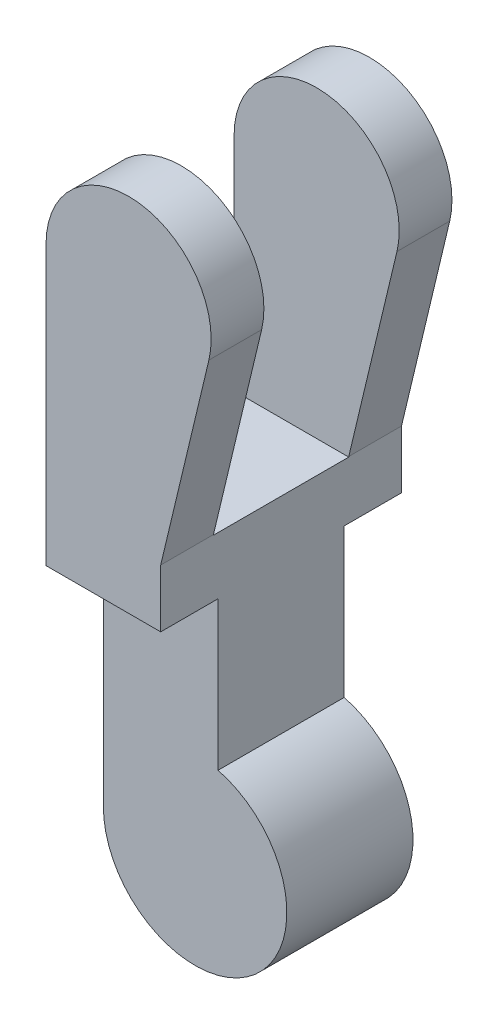
SolidWorks part; units mm, degrees
ref_plane "Front Plane" through (0, 0, 0) normal (0, 0, 1) x (1, 0, 0)
ref_plane "Top Plane" through (0, 0, 0) normal (0, 1, 0) x (1, 0, 0)
ref_plane "Right Plane" through (0, 0, 0) normal (1, 0, 0) x (0, 0, -1)
sketch "Sketch1" plane through (0, 0, 0) normal (0, 0, 1) x (1, 0, 0)
  line L0 (-80, 0) -> (-80, 450)
  line L1 (20, 257.4597) -> (20, 77.4597)
  line L2 (20, 257.4597) -> (62.0268, 433.2594)
  arc A0 (-80, 0) -> (20, 77.4597) centre (0, 0) ccw
  arc A1 (62.0268, 433.2594) -> (-80, 450) centre (-8, 450) ccw
  dimension "D1" = 160
  dimension "D3" = 144
  dimension "D2" = 450
  dimension "D4" = 180
  dimension "D5" = 100
extrude "Boss-Extrude1" add sketch "Sketch1" along normal mid plane 210
sketch "Sketch2" plane through (0, 0, 0) normal (1, 0, 0) x (0, 0, -1)
  line L0 (105, 522) -> (-105, 522) construction
  line L1 (-59, 522) -> (59, 522)
  line L2 (-59, 522) -> (-59, 257)
  line L3 (-59, 257) -> (59, 257)
  line L4 (59, 522) -> (59, 257)
  line L5 (-105, 77.4597) -> (-105, 257.4597) construction
  line L6 (-105, 207) -> (-55, 207)
  line L7 (-105, 207) -> (-105, -80)
  line L8 (-105, -80) -> (-55, -80)
  line L9 (-55, 207) -> (-55, -80)
  line L10 (-105, -80) -> (105, -80) construction
  line L11 (0, 0) -> (0, 179.2888) construction
  line L12 (105, -80) -> (55, -80)
  line L13 (55, 207) -> (55, -80)
  line L14 (105, 207) -> (105, -80)
  line L15 (105, 207) -> (55, 207)
  point P6 (0, 257)
  dimension "D1" = 265
  dimension "D2" = 118
  dimension "D3" = 287
  dimension "D4" = 50
extrude "Cut-Extrude1" cut sketch "Sketch2" against normal through all both and the other way through all
